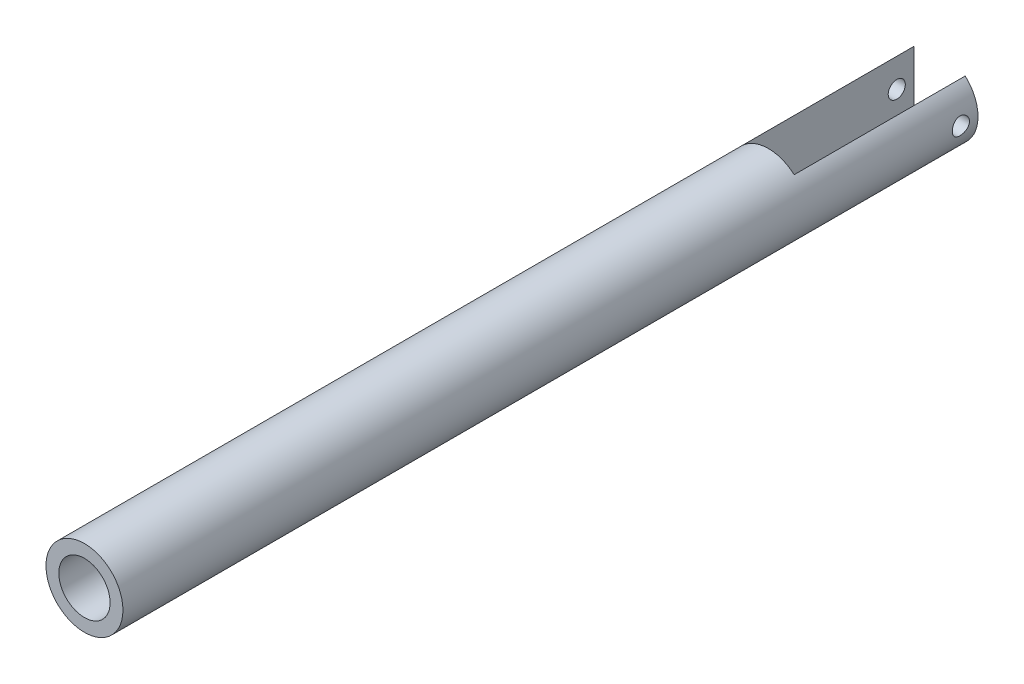
SolidWorks part; units mm, degrees
ref_plane "Front Plane" through (0, 0, 0) normal (0, 0, 1) x (1, 0, 0)
ref_plane "Top Plane" through (0, 0, 0) normal (0, 1, 0) x (1, 0, 0)
ref_plane "Right Plane" through (0, 0, 0) normal (1, 0, 0) x (0, 0, -1)
sketch "Sketch2" plane through (0, 0, 0) normal (0, 0, 1) x (1, 0, 0)
  circle A0 centre (0, 0) radius 3
  circle A1 centre (0, 0) radius 4.5
  dimension "D1" = 6
  dimension "D2" = 9
extrude "Boss-Extrude1" add sketch "Sketch2" along normal blind 80
sketch "Sketch3" plane through (0, 0, 0) normal (0, 0, -1) x (-1, 0, 0)
  line L0 (0, 7) -> (0, -7) construction
  line L1 (3, 3.3541) -> (3, -3.3541)
  line L2 (-3, 3.3541) -> (-3, -3.3541)
  arc A0 (3, -3.3541) -> (3, 3.3541) centre (0, 0) ccw
  circle A1 centre (0, 0) radius 4.5
  arc A2 (-3, 3.3541) -> (-3, -3.3541) centre (0, 0) ccw
  dimension "D2" = 3
  dimension "D1" = 0
extrude "Boss-Extrude2" add sketch "Sketch3" along normal blind 20
sketch "Sketch4" plane through (3, 0, 0) normal (-1, 0, 0) x (0, 0, 1)
  line L0 (-20, -3.3541) -> (-20, 3.3541) construction
  circle A0 centre (-18, 0) radius 1
  dimension "D1" = 2
  dimension "D2" = 2
extrude "Cut-Extrude1" cut sketch "Sketch4" against normal through all both and the other way through all
ref_plane "Plane1" through (0, 0, 30) normal (0, 0, -1) x (-1, 0, 0)
ref_plane "Plane2" through (0, 0, 60) normal (0, 0, -1) x (-1, 0, 0)
sketch "Sketch7" plane through (0, 0, 30) normal (0, 0, -1) x (-1, 0, 0)
  circle A0 centre (0, 0) radius 3 construction
  circle A1 centre (0, 0) radius 3
  circle A2 centre (0, 0) radius 1
  dimension "D1" = 2
extrude "Boss-Extrude3" add sketch "Sketch7" along normal blind 2
sketch "Sketch10" plane through (0, 0, 60) normal (0, 0, -1) x (-1, 0, 0)
  circle A0 centre (0, 0) radius 3 construction
  circle A1 centre (0, 0) radius 1 construction
  circle A2 centre (0, 0) radius 3
  circle A3 centre (0, 0) radius 1
extrude "Boss-Extrude4" add sketch "Sketch10" against normal blind 2
